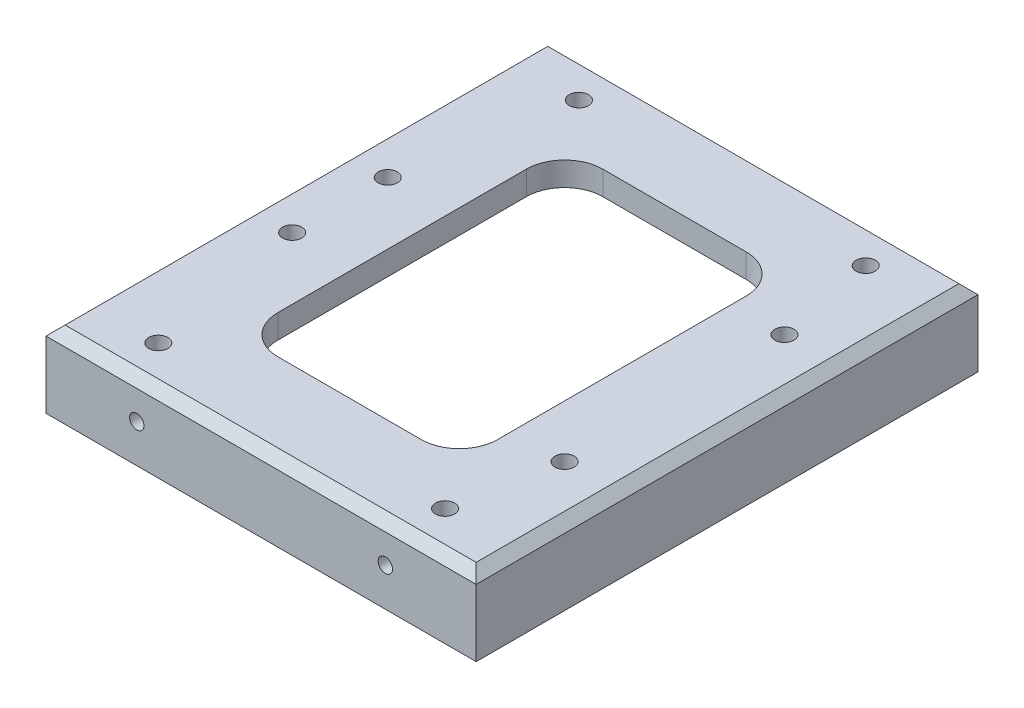
SolidWorks part; units mm, degrees
ref_plane "Front Plane" through (0, 0, 0) normal (0, 0, 1) x (1, 0, 0)
ref_plane "Top Plane" through (0, 0, 0) normal (0, 1, 0) x (1, 0, 0)
ref_plane "Right Plane" through (0, 0, 0) normal (1, 0, 0) x (0, 0, -1)
sketch "Sketch1" plane through (0, 0, 0) normal (0, 1, 0) x (1, 0, 0)
  line L1 (-45, 52.5) -> (45, 52.5)
  line L2 (-45, 52.5) -> (-45, -52.5)
  line L3 (-45, -52.5) -> (45, -52.5)
  line L4 (45, 52.5) -> (45, -52.5)
  line L5 (-45, 52.5) -> (45, -52.5) construction
  line L6 (-45, -52.5) -> (45, 52.5) construction
  point P0 (0, 0)
  dimension "D1" = 105
  dimension "D2" = 90
extrude "Boss-Extrude1" add sketch "Sketch1" along normal blind 16
chamfer "Chamfer1" distance 2 angle 45 4 edges at (45, 16, 0) (0, 16, 52.5) (-45, 16, 0) (0, 16, -52.5)
sketch "Sketch3" plane through (0, 0, 0) normal (0, -1, 0) x (1, 0, 0)
  line L0 (-45, -52.5) -> (-45, 52.5) construction
  line L1 (-40, 47.5) -> (40, 47.5)
  line L2 (-40, 47.5) -> (-40, -47.5)
  line L3 (-40, -47.5) -> (40, -47.5)
  line L4 (40, 47.5) -> (40, -47.5)
  line L5 (-40, 47.5) -> (40, -47.5) construction
  line L6 (-40, -47.5) -> (40, 47.5) construction
  line L7 (-45, 52.5) -> (45, 52.5) construction
  point P0 (0, 0)
  dimension "D1" = 5
  dimension "D2" = 5
extrude "Cut-Extrude1" cut sketch "Sketch3" against normal blind 11
sketch "Sketch4" plane through (0, 16, 0) normal (0, 1, 0) x (1, 0, 0)
  line L1 (-15, 34) -> (15, 34)
  line L2 (-23, 26) -> (-23, -26)
  line L3 (-15, -34) -> (15, -34)
  line L4 (23, 26) -> (23, -26)
  line L5 (-23, 34) -> (23, -34) construction
  line L6 (-23, -34) -> (23, 34) construction
  arc A0 (15, -34) -> (23, -26) centre (15, -26) ccw
  arc A1 (-23, -26) -> (-15, -34) centre (-15, -26) ccw
  arc A2 (15, 34) -> (23, 26) centre (15, 26) cw
  arc A3 (-15, 34) -> (-23, 26) centre (-15, 26) ccw
  point P0 (0, 0)
  dimension "D3" = 8
  dimension "D1" = 46
  dimension "D2" = 68
extrude "Cut-Extrude2" cut sketch "Sketch4" against normal through all
sketch "Sketch5" plane through (0, 16, 0) normal (0, 1, 0) x (1, 0, 0)
  line L0 (-45, -52.5) -> (-45, 52.5) construction
  line L1 (15, 34) -> (-15, 34) construction
  line L3 (45, 52.5) -> (45, -52.5) construction
  line L4 (-45, 52.5) -> (45, 52.5) construction
  line L5 (45, -52.5) -> (-45, -52.5) construction
  circle A0 centre (-30, 44) radius 2
  circle A1 centre (-30, -44) radius 2
  circle A2 centre (30, -44) radius 2
  circle A3 centre (30, 44) radius 2
  circle A4 centre (-36, -10) radius 2
  circle A5 centre (34, 23) radius 2
  circle A6 centre (-36, 10) radius 2
  circle A7 centre (34, -23) radius 2
  point P18 (0, 0)
  point P20 (-38.5507, 52.5)
  dimension "D1" = 4
  dimension "D3" = 8.5
  dimension "D10" = 42.5
  dimension "D2" = 15
  dimension "D4" = 8.5
  dimension "D5" = 15
  dimension "D6" = 15
  dimension "D7" = 8.5
  dimension "D8" = 8.5
  dimension "D9" = 15
  dimension "D11" = 9
  dimension "D12" = 20
  dimension "D13" = 46
  dimension "D14" = 11
  dimension "D15" = 11
extrude "Cut-Extrude3" cut sketch "Sketch5" against normal through all
sketch "Sketch6" plane through (0, 0, 52.5) normal (0, 0, 1) x (1, 0, 0)
  line L0 (-45, 14) -> (-45, 0) construction
  line L1 (-45, 0) -> (45, 0) construction
  circle A0 centre (-26, 8) radius 1.5
  circle A1 centre (26, 8) radius 1.5
  point P6 (-45, 7)
  dimension "D4" = 3
  dimension "D1" = 52
  dimension "D2" = 19
  dimension "D3" = 8
extrude "Cut-Extrude4" cut sketch "Sketch6" against normal up to surface (5 mm away) up to face at (0, 5.5, 47.5)
